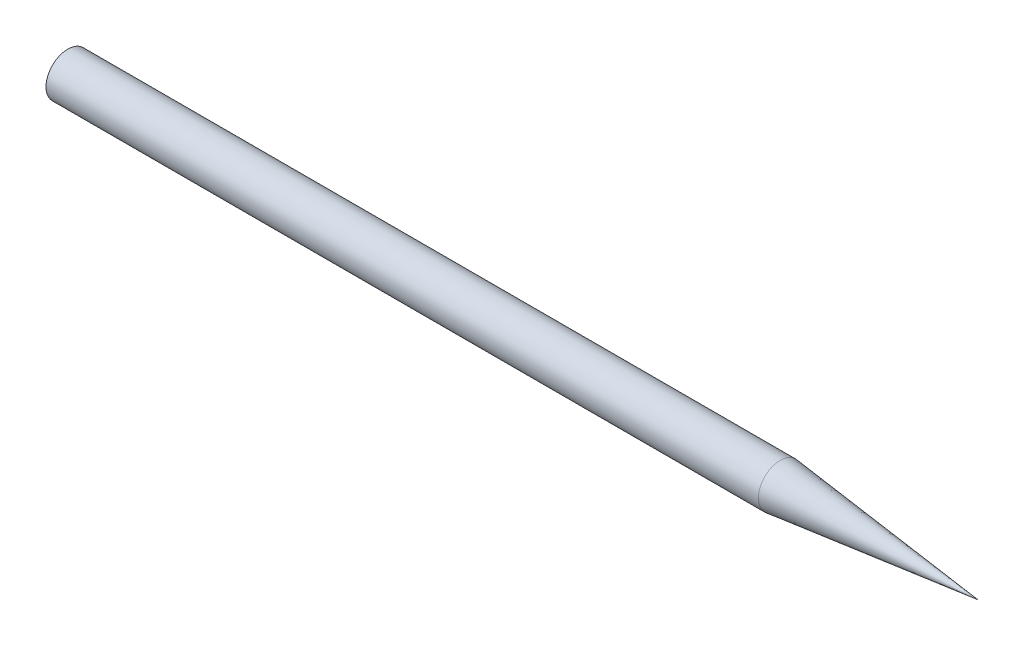
SolidWorks part; units mm, degrees
ref_plane "前视基准面" through (0, 0, 0) normal (0, 0, 1) x (1, 0, 0)
ref_plane "上视基准面" through (0, 0, 0) normal (0, 1, 0) x (1, 0, 0)
ref_plane "右视基准面" through (0, 0, 0) normal (1, 0, 0) x (0, 0, -1)
sketch "草图1" plane through (0, 0, 0) normal (0, 0, 1) x (1, 0, 0)
  line L0 (18, 0) -> (23, 0)
  line L1 (0, 0) -> (18, 0)
  line L2 (0, 0) -> (0, 0.55)
  line L3 (0, 0.55) -> (18, 0.55)
  line L4 (18, 0) -> (18, 0.55)
  line L5 (23, 0) -> (18, 0.55)
  dimension "D1" = 23
  dimension "18" = 18
  dimension "0.55" = 0.55
revolve "旋转1" add sketch "草图1" angle 360 about L1
